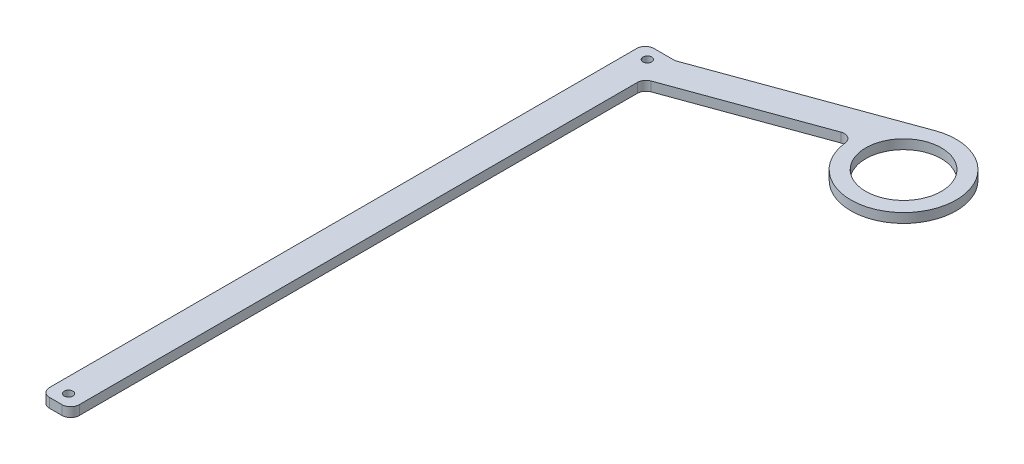
SolidWorks part; units mm, degrees
ref_plane "Front Plane" through (0, 0, 0) normal (0, 0, 1) x (1, 0, 0)
ref_plane "Top Plane" through (0, 0, 0) normal (0, 1, 0) x (1, 0, 0)
ref_plane "Right Plane" through (0, 0, 0) normal (1, 0, 0) x (0, 0, -1)
sketch "Sketch1" plane through (0, 0, 0) normal (0, 1, 0) x (1, 0, 0)
  line L0 (5, -101.6) -> (5, 90.9582)
  line L1 (-5, 101.6) -> (5, 101.6)
  line L2 (-5, 101.6) -> (-5, -101.6)
  line L3 (-5, -101.6) -> (5, -101.6)
  line L5 (-5, 101.6) -> (5, -101.6) construction
  line L6 (-5, -101.6) -> (5, 101.6) construction
  line L8 (69.0706, 124.9198) -> (5, 101.6)
  line L9 (0, -97.28) -> (0, 0) construction
  line L10 (0, 97.28) -> (0, 0) construction
  line L11 (5, 90.9582) -> (57.5145, 110.0719)
  circle A0 centre (0, -97.28) radius 1.4605
  circle A1 centre (0, 97.28) radius 1.4605
  circle A2 centre (75.1243, 108.2872) radius 12.7
  arc A3 (69.0706, 124.9198) -> (57.5145, 110.0719) centre (75.1243, 108.2872) cw
  point P0 (0, 0)
  point P14 (0, 0)
  point P16 (0, 0)
  point P17 (0, 0)
  point P18 (0, 0)
  point P19 (61.7917, 122.2705)
  point P20 (0, 0)
  dimension "D6" = 2.921
  dimension "D8" = 25.4
  dimension "D1" = 203.2
  dimension "D2" = 10
  dimension "D3" = 10
  dimension "D4" = 160
  dimension "D7" = 194.56
  dimension "D9" = 5
  dimension "D10" = 55.8848
extrude "Boss-Extrude1" add sketch "Sketch1" along normal blind 3.175
fillet "Fillet1" radius 2.921 6 edges at (5, 1.5875, -101.6) (-5, 1.5875, -101.6) (-5, 1.5875, 101.6) (5, 1.5875, 101.6) (5, 1.5875, -90.9582) (57.5145, 1.5875, -110.0719)
